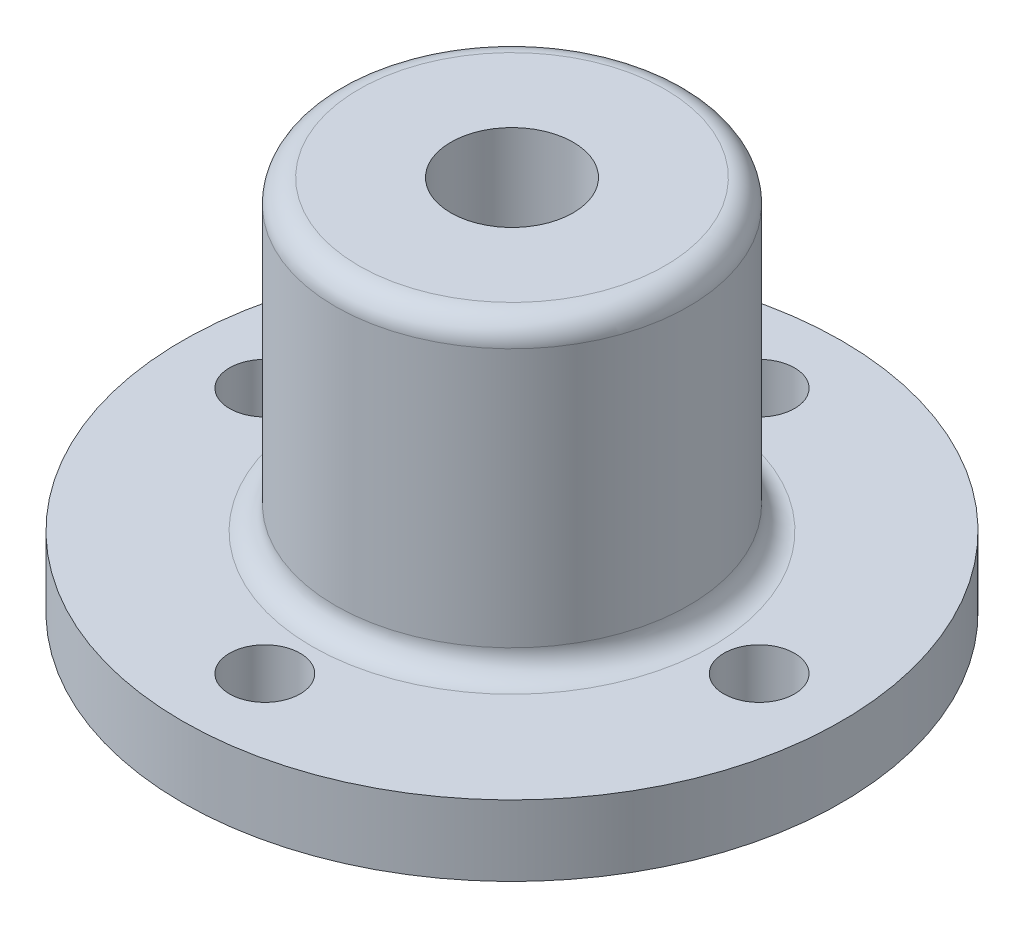
SolidWorks part; units mm, degrees
ref_plane "Front Plane" through (0, 0, 0) normal (0, 0, 1) x (1, 0, 0)
ref_plane "Top Plane" through (0, 0, 0) normal (0, 1, 0) x (1, 0, 0)
ref_plane "Right Plane" through (0, 0, 0) normal (1, 0, 0) x (0, 0, -1)
sketch "Sketch1" plane through (0, 0, 0) normal (0, 1, 0) x (1, 0, 0)
  line L0 (-2.25, 1.0897) -> (-2.25, -1.0897) construction
  line L1 (-2.35, 1.1124) -> (-2.35, -1.1124)
  circle A0 centre (0, 0) radius 14
  arc A1 (-2.25, -1.0897) -> (-2.25, 1.0897) centre (0, 0) ccw construction
  circle A2 centre (0, 0) radius 10.5 construction
  circle A3 centre (0, 10.5) radius 1.5
  circle A4 centre (10.5, 0) radius 1.5
  circle A5 centre (0, -10.5) radius 1.5
  circle A6 centre (-10.5, 0) radius 1.5
  arc A7 (-2.35, -1.1124) -> (-2.35, 1.1124) centre (0, 0) ccw
  point P16 (0, 0)
  dimension "D1" = 28
  dimension "D2" = 5
  dimension "D3" = 21
  dimension "D4" = 3
  dimension "D6" = 2.25
  dimension "D7" = 0.1
  dimension "D5" = 4
extrude "Boss-Extrude1" add sketch "Sketch1" along normal blind 3
sketch "Sketch2" plane through (0, 3, 0) normal (0, 1, 0) x (1, 0, 0)
  line L1 (-2.35, 1.1124) -> (-2.35, -1.1124)
  line L2 (-2.35, 1.1124) -> (-2.35, -1.1124) construction
  circle A0 centre (0, 0) radius 7.5
  arc A2 (-2.35, -1.1124) -> (-2.35, 1.1124) centre (0, 0) ccw
  arc A4 (-2.35, -1.1124) -> (-2.35, 1.1124) centre (0, 0) ccw construction
  point P4 (-0.25, 0)
  point P5 (0, 0)
  dimension "D1" = 15
extrude "Boss-Extrude2" add sketch "Sketch2" along normal blind 13
fillet "Fillet1" radius 1 2 edges at (0, 16, 7.5) (0, 3, 7.5)
sketch "Sketch4" plane through (0, 16, 0) normal (0, 1, 0) x (1, 0, 0)
  circle A0 centre (0, 0) radius 2.6
  arc A1 (-2.35, -1.1124) -> (-2.35, 1.1124) centre (0, 0) ccw construction
extrude "Cut-Extrude2" cut sketch "Sketch4" against normal blind 6
